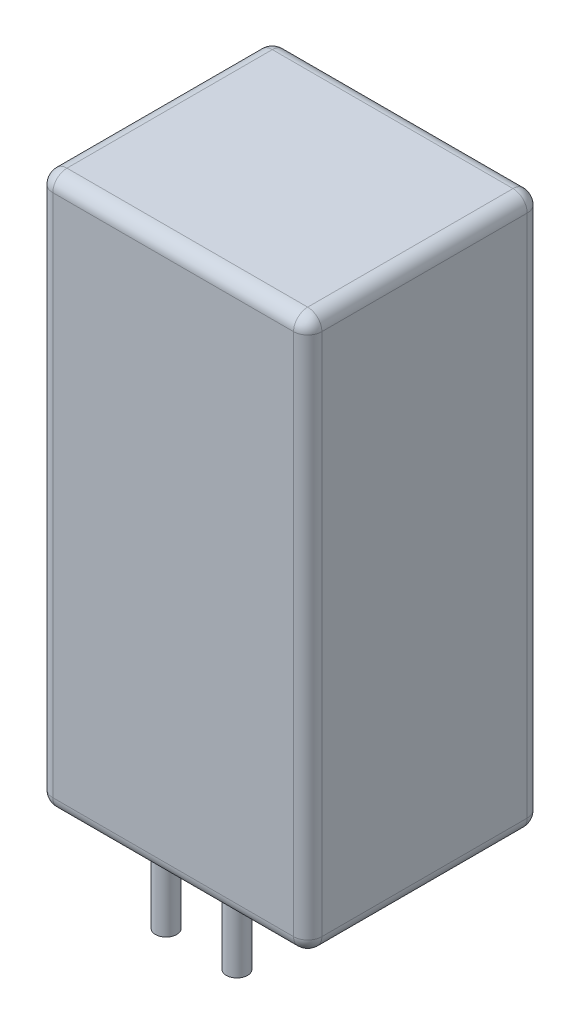
SolidWorks part; units mm, degrees
ref_plane "前视基准面" through (0, 0, 0) normal (0, 0, 1) x (1, 0, 0)
ref_plane "上视基准面" through (0, 0, 0) normal (0, 1, 0) x (1, 0, 0)
ref_plane "右视基准面" through (0, 0, 0) normal (1, 0, 0) x (0, 0, -1)
other "Configuration Table"
sketch "草图1" plane through (0, 0, 0) normal (0, 1, 0) x (1, 0, 0)
  line L1 (19, 16.5) -> (-19, 16.5)
  line L2 (19, 16.5) -> (19, -16.5)
  line L3 (19, -16.5) -> (-19, -16.5)
  line L4 (-19, 16.5) -> (-19, -16.5)
  line L5 (0, -16.5) -> (0, 16.5) construction
  line L6 (19, 0) -> (-19, 0) construction
  point P0 (0, 0)
  dimension "D1" = 33
  dimension "D2" = 38
extrude "凸台-拉伸1" add sketch "草图1" along normal blind 78
fillet "圆角1" radius 2 12 edges at (-19, 39, 16.5) (19, 39, 16.5) (19, 39, -16.5) (-19, 39, -16.5) (0, 78, -16.5) (19, 78, 0) (0, 78, 16.5) (-19, 78, 0) (0, 0, -16.5) (19, 0, 0) (0, 0, 16.5) (-19, 0, 0)
sketch "草图2" plane through (0, 0, 0) normal (0, -1, 0) x (1, 0, 0)
  line L0 (0, 0) -> (0, 50000) construction
  line L1 (-17, 16.5) -> (17, 16.5) construction
  circle A0 centre (-5, 12.5) radius 1.5
  circle A1 centre (5, 12.5) radius 1.5
  dimension "D1" = 4
  dimension "D2" = 3
  dimension "D3" = 10
extrude "凸台-拉伸2" add sketch "草图2" along normal blind 10 separate body
